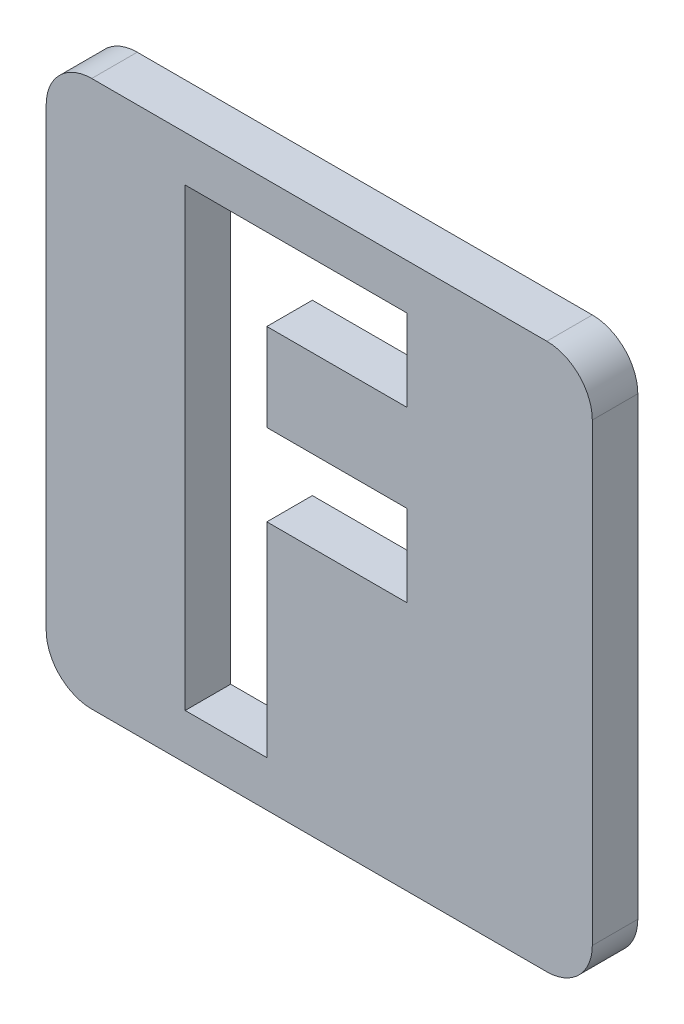
SolidWorks part; units mm, degrees
ref_plane "Front Plane" through (0, 0, 0) normal (0, 0, 1) x (1, 0, 0)
ref_plane "Top Plane" through (0, 0, 0) normal (0, 1, 0) x (1, 0, 0)
ref_plane "Right Plane" through (0, 0, 0) normal (1, 0, 0) x (0, 0, -1)
sketch "Sketch1" plane through (0, 0, 0) normal (0, 0, 1) x (1, 0, 0)
  line L1 (-50, 60) -> (50, 60)
  line L2 (-60, 50) -> (-60, -50)
  line L3 (-50, -60) -> (50, -60)
  line L4 (60, 50) -> (60, -50)
  line L5 (-60, 60) -> (60, -60) construction
  line L6 (-60, -60) -> (60, 60) construction
  arc A0 (-60, -50) -> (-50, -60) centre (-50, -50) ccw
  arc A1 (50, -60) -> (60, -50) centre (50, -50) ccw
  arc A2 (50, 60) -> (60, 50) centre (50, 50) cw
  arc A3 (-50, 60) -> (-60, 50) centre (-50, 50) ccw
  point P0 (0, 0)
  dimension "D3" = 10
  dimension "D1" = 120
  dimension "D2" = 120
extrude "Boss-Extrude1" add sketch "Sketch1" along normal blind 10 contours A3 L2 A0 L3 A1 L4 A2 L1
sketch "Sketch2" plane through (0, 0, 10) normal (0, 0, 1) x (1, 0, 0)
  line L0 (0, 0) -> (0, 40) construction
  line L1 (-50, 50) -> (50, 50) construction
  line L2 (-50, 50) -> (-50, -50) construction
  line L3 (-50, -50) -> (50, -50) construction
  line L4 (50, 50) -> (50, -50) construction
  line L5 (-50, 50) -> (50, -50) construction
  line L6 (-50, -50) -> (50, 50) construction
  line L7 (0, 40) -> (-40, 40) construction
  line L8 (-40, 40) -> (-40, 0) construction
  line L9 (-40, 0) -> (0, 0) construction
  line L11 (0, 20) -> (-20, 20) construction
  line L12 (-20, 40) -> (-20, 20) construction
  circle A0 centre (0, 40) radius 4 construction
  circle A1 centre (0, 20) radius 4 construction
  circle A2 centre (0, 0) radius 4 construction
  circle A3 centre (-20, 20) radius 4 construction
  circle A4 centre (-20, 40) radius 4 construction
  circle A5 centre (-40, 40) radius 4 construction
  circle A6 centre (0, 0) radius 4 construction
  circle A7 centre (20, 0) radius 4 construction
  circle A8 centre (40, 0) radius 4 construction
  circle A9 centre (40, 20) radius 4 construction
  circle A10 centre (40, 40) radius 4 construction
  circle A11 centre (20, 20) radius 4 construction
  circle A12 centre (0, 0) radius 4 construction
  circle A13 centre (0, -20) radius 4 construction
  circle A14 centre (0, -40) radius 4 construction
  circle A15 centre (20, -40) radius 4 construction
  circle A16 centre (40, -40) radius 4 construction
  circle A17 centre (20, -20) radius 4 construction
  circle A18 centre (0, 0) radius 4 construction
  circle A19 centre (-20, 0) radius 4 construction
  circle A20 centre (-40, 0) radius 4 construction
  circle A21 centre (-40, -20) radius 4 construction
  circle A22 centre (-40, -40) radius 4 construction
  circle A23 centre (-20, -20) radius 4 construction
  text T0 "F" font "Century Gothic" height 100
  point P0 (0, 0)
  point P55 (0, 0)
  dimension "D4" = 8
  dimension "D1" = 100
  dimension "D2" = 100
  dimension "D3" = 40
  dimension "D5" = 4
extrude "Cut-Extrude19" cut sketch "Sketch2" against normal blind 10
